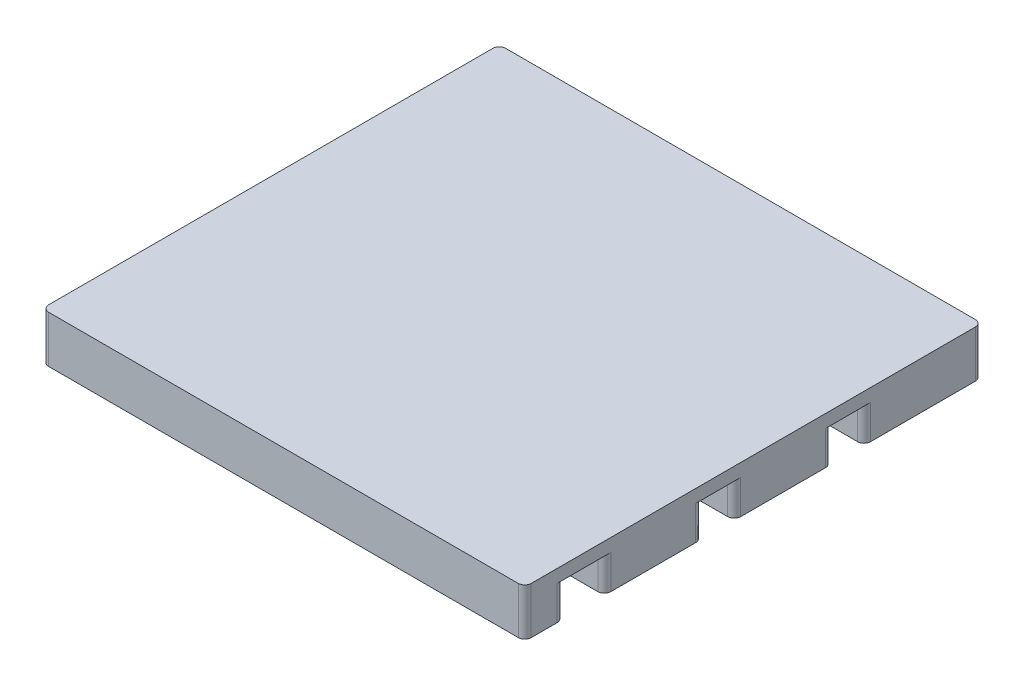
SolidWorks part; units mm, degrees
ref_plane "Front Plane" through (0, 0, 0) normal (0, 0, 1) x (1, 0, 0)
ref_plane "Top Plane" through (0, 0, 0) normal (0, 1, 0) x (1, 0, 0)
ref_plane "Right Plane" through (0, 0, 0) normal (1, 0, 0) x (0, 0, -1)
sketch "Sketch3" plane through (0, 0, 0) normal (0, 1, 0) x (1, 0, 0)
  line L1 (0, 0) -> (149, 0)
  line L2 (0, 0) -> (0, -141.12)
  line L3 (0, -141.12) -> (149, -141.12)
  line L4 (149, 0) -> (149, -141.12)
  dimension "D1" = 141.12
  dimension "D2" = 149
extrude "Boss-Extrude1" add sketch "Sketch3" along normal blind 4
sketch "Sketch5" plane through (0, 4, 0) normal (0, 1, 0) x (1, 0, 0)
  line L0 (0, 0) -> (0, -141.12) construction
  line L1 (149, 0) -> (82, 0)
  line L2 (149, 0) -> (149, -36.35)
  line L3 (149, -36.35) -> (82, -36.35)
  line L4 (82, 0) -> (82, -36.35)
  line L5 (0, -8.7) -> (67, -8.7)
  line L6 (0, -8.7) -> (0, -38.9)
  line L7 (0, -38.9) -> (67, -38.9)
  line L8 (67, -8.7) -> (67, -38.9)
  line L9 (149, 0) -> (0, 0) construction
  line L10 (149, -141.12) -> (149, 0) construction
  line L11 (0, -48.8) -> (67, -48.8)
  line L12 (0, -48.8) -> (0, -79)
  line L13 (0, -79) -> (67, -79)
  line L14 (67, -48.8) -> (67, -79)
  line L15 (0, -88.9) -> (67, -88.9)
  line L16 (0, -88.9) -> (0, -119.1)
  line L17 (0, -119.1) -> (67, -119.1)
  line L18 (67, -88.9) -> (67, -119.1)
  line L19 (149, -46.25) -> (82, -46.25)
  line L20 (149, -46.25) -> (149, -76.45)
  line L21 (149, -76.45) -> (82, -76.45)
  line L22 (82, -46.25) -> (82, -76.45)
  line L23 (13, -8.7) -> (13, -21.7) construction
  line L24 (149, -86.35) -> (82, -86.35)
  line L25 (149, -86.35) -> (149, -116.55)
  line L26 (149, -116.55) -> (82, -116.55)
  line L27 (82, -86.35) -> (82, -116.55)
  line L28 (13, -21.7) -> (13, -27.9) construction
  line L29 (13, -27.9) -> (13, -38.9) construction
  line L30 (13, -21.7) -> (41, -21.7)
  line L31 (13, -27.9) -> (41, -27.9)
  line L32 (13, -48.8) -> (13, -61.8) construction
  line L33 (13, -61.8) -> (13, -68) construction
  line L34 (13, -68) -> (13, -79) construction
  line L35 (13, -61.8) -> (41, -61.8)
  line L36 (13, -68) -> (41, -68)
  line L37 (97, -36.35) -> (97, -25.35) construction
  line L38 (97, -25.35) -> (97, -19.15) construction
  line L39 (97, -19.15) -> (97, 0) construction
  line L40 (97, -19.15) -> (125, -19.15)
  line L41 (97, -25.35) -> (125, -25.35)
  line L42 (97, -46.25) -> (97, -59.25) construction
  line L43 (97, -59.25) -> (97, -65.45) construction
  line L44 (97, -65.45) -> (97, -76.45) construction
  line L45 (97, -59.25) -> (125, -59.25)
  line L46 (97, -65.45) -> (125, -65.45)
  line L47 (13, -88.9) -> (13, -101.9) construction
  line L48 (13, -101.9) -> (13, -108.1) construction
  line L49 (13, -108.1) -> (13, -119.1) construction
  line L50 (13, -101.9) -> (41, -101.9)
  line L51 (13, -108.1) -> (41, -108.1)
  line L52 (97, -86.35) -> (97, -99.35) construction
  line L53 (97, -99.35) -> (97, -105.55) construction
  line L54 (97, -105.55) -> (97, -116.55) construction
  line L55 (97, -99.35) -> (125, -99.35)
  line L56 (97, -105.55) -> (125, -105.55)
  arc A0 (13, -27.9) -> (13, -21.7) centre (13, -24.8) cw
  arc A1 (41, -21.7) -> (41, -27.9) centre (41, -24.8) cw
  arc A2 (13, -61.8) -> (13, -68) centre (13, -64.9) ccw
  arc A3 (41, -61.8) -> (41, -68) centre (41, -64.9) cw
  arc A4 (97, -25.35) -> (97, -19.15) centre (97, -22.25) cw
  arc A5 (125, -19.15) -> (125, -25.35) centre (125, -22.25) cw
  arc A6 (97, -65.45) -> (97, -59.25) centre (97, -62.35) cw
  arc A7 (125, -59.25) -> (125, -65.45) centre (125, -62.35) cw
  arc A8 (13, -101.9) -> (13, -108.1) centre (13, -105) ccw
  arc A9 (41, -101.9) -> (41, -108.1) centre (41, -105) cw
  arc A10 (97, -99.35) -> (97, -105.55) centre (97, -102.45) ccw
  arc A11 (125, -99.35) -> (125, -105.55) centre (125, -102.45) cw
  line M18 (0, 0) -> (0, -141.12)
  line M20 (149, -141.12) -> (149, 0)
  line M21 (149, 0) -> (0, 0)
  dimension "D1" = 67
  dimension "D2" = 36.35
  dimension "D3" = 67
  dimension "D4" = 30.2
  dimension "D5" = 8.7
  dimension "D6" = 30.2
  dimension "D7" = 9.9
  dimension "D8" = 9.9
  dimension "D9" = 30.2
  dimension "D10" = 9.9
  dimension "D11" = 30.2
  dimension "D12" = 9.9
  dimension "D13" = 30.2
  dimension "D14" = 67
  dimension "D15" = 67
  dimension "D16" = 67
  dimension "D17" = 67
  dimension "D18" = 13
  dimension "D19" = 11
  dimension "D20" = 13
  dimension "D21" = 28
  dimension "D22" = 13
  dimension "D23" = 11
  dimension "D24" = 28
  dimension "D26" = 11
  dimension "D27" = 24
  dimension "D28" = 28
  dimension "D29" = 11
  dimension "D30" = 13
  dimension "D31" = 13
  dimension "D32" = 11
  dimension "D33" = 13
  dimension "D34" = 11
extrude "Boss-Extrude2" add sketch "Sketch5" against normal blind 14.5 contours L8 L5 L7 L30 A1 L31 A0 M18 | L4 L3 L40 A5 L41 A4 M21 M20 | L14 L11 L13 L35 A3 L36 A2 M18 | L19 L22 L21 L45 A7 L46 A6 M20 | L18 L15 L17 L50 A9 L51 A8 M18 | L24 L27 L26 L55 A11 L56 A10 M20
fillet "Fillet1" radius 2 24 edges at (149, -5.25, 86.35) (82, -5.25, 86.35) (149, -5.25, 116.55) (82, -5.25, 116.55) (67, -5.25, 88.9) (67, -5.25, 119.1) (0, -5.25, 119.1) (0, -5.25, 88.9) (0, -5.25, 79) (82, -5.25, 76.45) (149, -5.25, 76.45) (149, -5.25, 46.25) (82, -5.25, 46.25) (67, -5.25, 48.8) (67, -5.25, 79) (0, -5.25, 48.8) (0, -5.25, 38.9) (67, -5.25, 38.9) (82, -5.25, 36.35) (149, -5.25, 36.35) (149, -3.25, 0) (82, -5.25, 0) (67, -5.25, 8.7) (0, -5.25, 8.7)
sketch "Sketch6" plane through (0, 0, 0) normal (0, -1, 0) x (1, 0, 0)
  line L0 (0, 129.12) -> (149, 129.12)
  line L1 (0, 117.1) -> (0, 141.12) construction
  line L2 (149, 141.12) -> (149, 114.55) construction
  line L3 (149, 129.12) -> (149, 141.12)
  line L4 (149, 141.12) -> (0, 141.12)
  line L5 (0, 141.12) -> (0, 129.12)
  dimension "D1" = 12
extrude "Boss-Extrude3" add sketch "Sketch6" along normal blind 10.5
fillet "Fillet2" radius 2 5 edges at (149, -5.25, 129.12) (0, -5.25, 129.12) (0, -3.25, 141.12) (149, -3.25, 141.12) (0, 2, 0)
